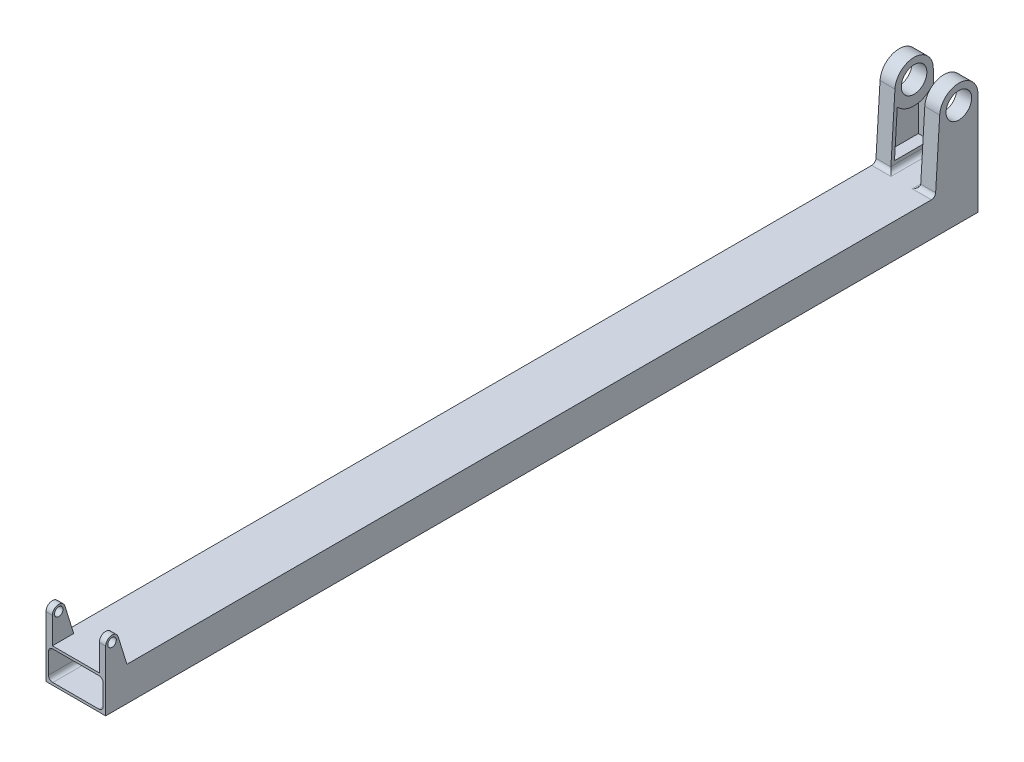
SolidWorks part; units mm, degrees
material "AISI 1045 Steel, cold drawn"
ref_plane "Front Plane" through (0, 0, 0) normal (0, 0, 1) x (1, 0, 0)
ref_plane "Top Plane" through (0, 0, 0) normal (0, 1, 0) x (1, 0, 0)
ref_plane "Right Plane" through (0, 0, 0) normal (1, 0, 0) x (0, 0, -1)
sketch "Sketch1" plane through (0, 0, 0) normal (1, 0, 0) x (0, 0, -1)
  line L0 (0, 0) -> (-2600, 0)
  line L1 (-2600, 0) -> (-2600, 101.6)
  line L2 (-2600, 101.6) -> (0, 101.6)
  line L3 (0, 101.6) -> (0, 0)
  line L4 (0, 101.6) -> (0, 304.8)
  line L5 (-114.1906, 308.3343) -> (-127, 101.6)
  arc A0 (0, 304.8) -> (-114.1906, 308.3343) centre (-57.15, 304.8) ccw
  circle A1 centre (-57.15, 304.8) radius 38.1
  dimension "D1" = 101.6
  dimension "D4" = 76.2
  dimension "D2" = 2600
  dimension "D3" = 203.2
  dimension "D5" = 19.05
  dimension "D6" = 69.85
sketch "Sketch2" plane through (0, 0, 0) normal (0, 0, 1) x (1, 0, 0)
  line L0 (0, 101.6) -> (0, 0) construction
  line L1 (0, 101.6) -> (-177.8, 101.6)
  line L2 (0, 101.6) -> (0, 0)
  line L3 (0, 0) -> (-177.8, 0)
  line L4 (-177.8, 101.6) -> (-177.8, 0)
  line L5 (0, 101.6) -> (0, 304.8) construction
  line L6 (-7.5, 94.1) -> (-7.5, 7.5)
  line L7 (-7.5, 7.5) -> (-170.3, 7.5)
  line L8 (-170.3, 94.1) -> (-170.3, 7.5)
  line L9 (-7.5, 94.1) -> (-170.3, 94.1)
  dimension "D1" = 101.6
  dimension "D2" = 177.8
  dimension "D3" = 7.5
extrude "Boss-Extrude2" add sketch "Sketch2" along normal up to vertex (2600 mm away) up to point (0, 101.6, 2600)
extrude "Boss-Extrude3" add sketch "Sketch1" against normal blind 44.45 contours L4 A0 L5 L2 A1
ref_plane "Plane1" through (-177.8, 0, 0) normal (-1, 0, 0) x (0, 0, 1)
sketch "Sketch3" plane through (-177.8, 0, 0) normal (-1, 0, 0) x (0, 0, 1)
  line L3 (0, 304.8) -> (0, 101.6)
  line L4 (0, 101.6) -> (127, 101.6)
  line L5 (127, 101.6) -> (114.1906, 308.3343)
  line L6 (0, 304.8) -> (0, 101.6)
  line L7 (0, 101.6) -> (127, 101.6)
  line L8 (127, 101.6) -> (114.1906, 308.3343)
  circle A0 centre (57.15, 304.8) radius 38.1 construction
  arc A1 (114.1906, 308.3343) -> (0, 304.8) centre (57.15, 304.8) ccw
  arc A2 (114.1906, 308.3343) -> (0, 304.8) centre (57.15, 304.8) ccw
  circle A3 centre (57.15, 304.8) radius 38.1
  dimension "D1" = 0
extrude "Boss-Extrude5" add sketch "Sketch3" against normal blind 44.45
fillet "Fillet1" radius 12.7 4 edges at (-7.5, 7.5, 1300) (-7.5, 94.1, 1300) (-170.3, 94.1, 1300) (-170.3, 7.5, 1300)
fillet "Fillet2" radius 12.7 4 edges at (-155.575, 101.6, 127) (-22.225, 101.6, 127) (-133.35, 101.6, 63.5) (-44.45, 101.6, 63.5)
sketch "Sketch5" plane through (0, 0, 0) normal (1, 0, 0) x (0, 0, -1)
  line L0 (-2600, 101.6) -> (-2600, 180.34)
  line L1 (-2562.7601, 185.9996) -> (-2536.5, 101.6)
  line L2 (-2600, 101.6) -> (-138.9375, 101.6) construction
  line L3 (-2536.5, 101.6) -> (-2600, 101.6)
  arc A0 (-2600, 180.34) -> (-2562.7601, 185.9996) centre (-2580.95, 180.34) cw
  circle A1 centre (-2580.95, 180.34) radius 12.7
  dimension "D3" = 6.35
  dimension "D4" = 25.4
  dimension "D1" = 78.74
  dimension "D2" = 63.5
extrude "Boss-Extrude7" add sketch "Sketch5" against normal blind 19.05
sketch "Sketch7" plane through (0, 0, 2600) normal (0, 0, 1) x (1, 0, 0)
  line L0 (-177.8, 101.6) -> (0, 101.6) construction
  point P4 (-88.9, 101.6)
ref_plane "Plane3" through (-88.9, 0, 0) normal (-1, 0, 0) x (0, 0, 1)
mirror "Mirror1" about plane through (-88.9, 0, 0) normal (-1, 0, 0) of "Boss-Extrude7"
sketch "Sketch8" plane through (-133.35, 0, 0) normal (1, 0, 0) x (0, 0, -1)
  line L3 (-114.1906, 308.3343) -> (-126.2131, 114.3)
  line L4 (-126.2131, 114.3) -> (0, 114.3)
  line L5 (0, 114.3) -> (0, 304.8)
  line L6 (-114.1906, 308.3343) -> (-126.2131, 114.3)
  line L7 (-126.2131, 114.3) -> (0, 114.3)
  line L8 (0, 114.3) -> (0, 304.8)
  line L12 (-104.2098, 307.7159) -> (-115.5743, 124.3)
  line L13 (-115.5743, 124.3) -> (-10, 124.3)
  line L14 (-10, 124.3) -> (-10, 304.8)
  line L15 (-104.2098, 307.7159) -> (-115.5743, 124.3)
  line L16 (-115.5743, 124.3) -> (-10, 124.3)
  line L17 (-10, 124.3) -> (-10, 304.8)
  arc A1 (0, 304.8) -> (-114.1906, 308.3343) centre (-57.15, 304.8) ccw
  arc A2 (0, 304.8) -> (-114.1906, 308.3343) centre (-57.15, 304.8) ccw
  arc A4 (-10, 304.8) -> (-104.2098, 307.7159) centre (-57.15, 304.8) ccw
  arc A5 (-10, 304.8) -> (-104.2098, 307.7159) centre (-57.15, 304.8) ccw
  circle A7 centre (-57.15, 304.8) radius 68.1
  circle A8 centre (-57.15, 304.8) radius 68.1
  dimension "D1" = 0
  dimension "D2" = 10
  dimension "D3" = 30
extrude "Cut-Extrude1" cut sketch "Sketch8" against normal offset from surface (34.45 mm away) 10 contours A8 L15 L16 L17 up to face at (-177.8, 151.6708, 1186.3343)
sketch "Sketch9" plane through (0, 101.6, 0) normal (0, 1, 0) x (1, 0, 0)
  line L0 (-57.15, 0) -> (-120.65, 0) construction
  line L1 (-88.9, 0) -> (0, 0)
  line L2 (-88.9, 0) -> (-88.9, -2600)
  line L3 (-88.9, -2600) -> (0, -2600)
  line L4 (0, 0) -> (0, -2600)
extrude "Cut-Extrude2" cut sketch "Sketch9" against normal through all both and the other way through all
mirror "Mirror2" about plane through (-88.9, 0, 0) normal (-1, 0, 0) of bodies 111
equation "\"D1@Sketch2\"=\"D1@Sketch1\""
